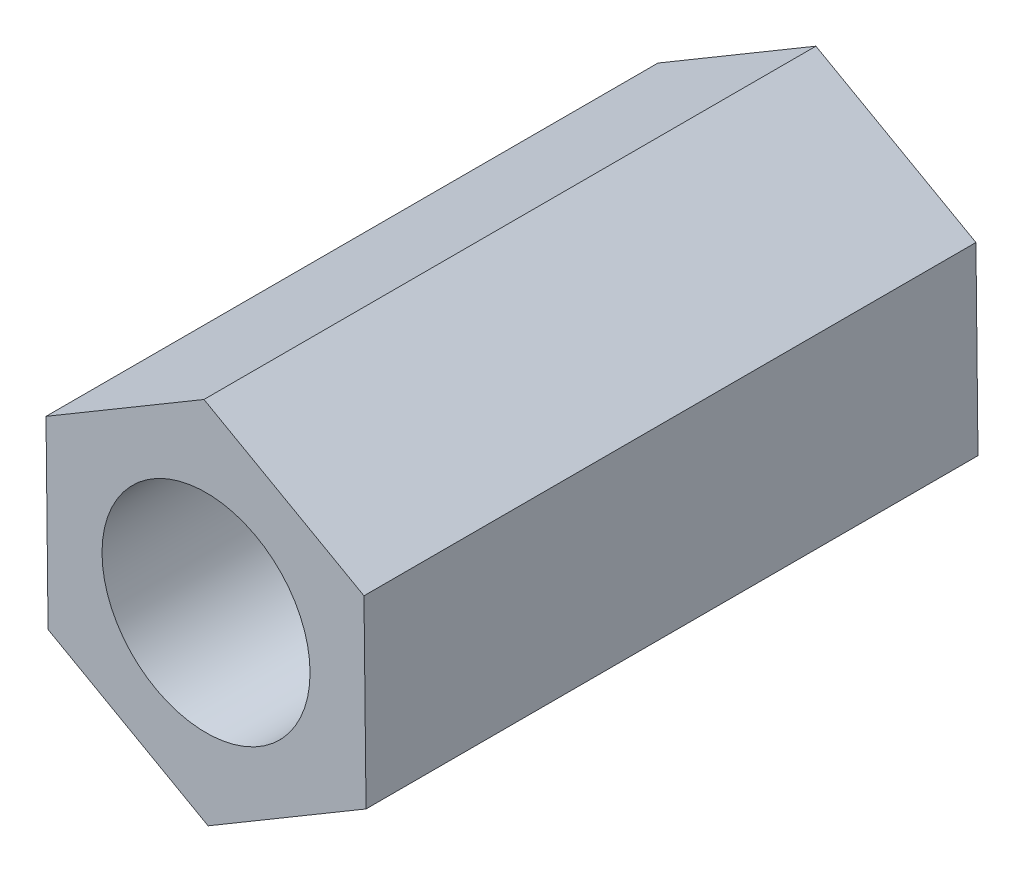
SolidWorks part; units mm, degrees
ref_plane "Front Plane" through (0, 0, 0) normal (0, 0, 1) x (1, 0, 0)
ref_plane "Top Plane" through (0, 0, 0) normal (0, 1, 0) x (1, 0, 0)
ref_plane "Right Plane" through (0, 0, 0) normal (1, 0, 0) x (0, 0, -1)
sketch "Sketch1" plane through (0, 0, 0) normal (0, 0, 1) x (1, 0, 0)
  circle A0 centre (0, 0) radius 8.5
  dimension "D1" = 17
sketch "Sketch2" plane through (0, 0, 0) normal (0, 0, 1) x (1, 0, 0)
  line L1 (12.9058, 7.6466) -> (-0.1692, 15)
  line L2 (-0.1692, 15) -> (-13.075, 7.3534)
  line L3 (-13.075, 7.3534) -> (-12.9058, -7.6466)
  line L4 (-12.9058, -7.6466) -> (0.1692, -15)
  line L5 (0.1692, -15) -> (13.075, -7.3534)
  line L6 (13.075, -7.3534) -> (12.9058, 7.6466)
  circle A0 centre (0, 0) radius 12.9912 construction
  dimension "D1" = 15
extrude "Boss-Extrude1" add sketch "Sketch2" along normal mid plane 50
extrude "Cut-Extrude1" cut sketch "Sketch1" against normal through all both and the other way through all
